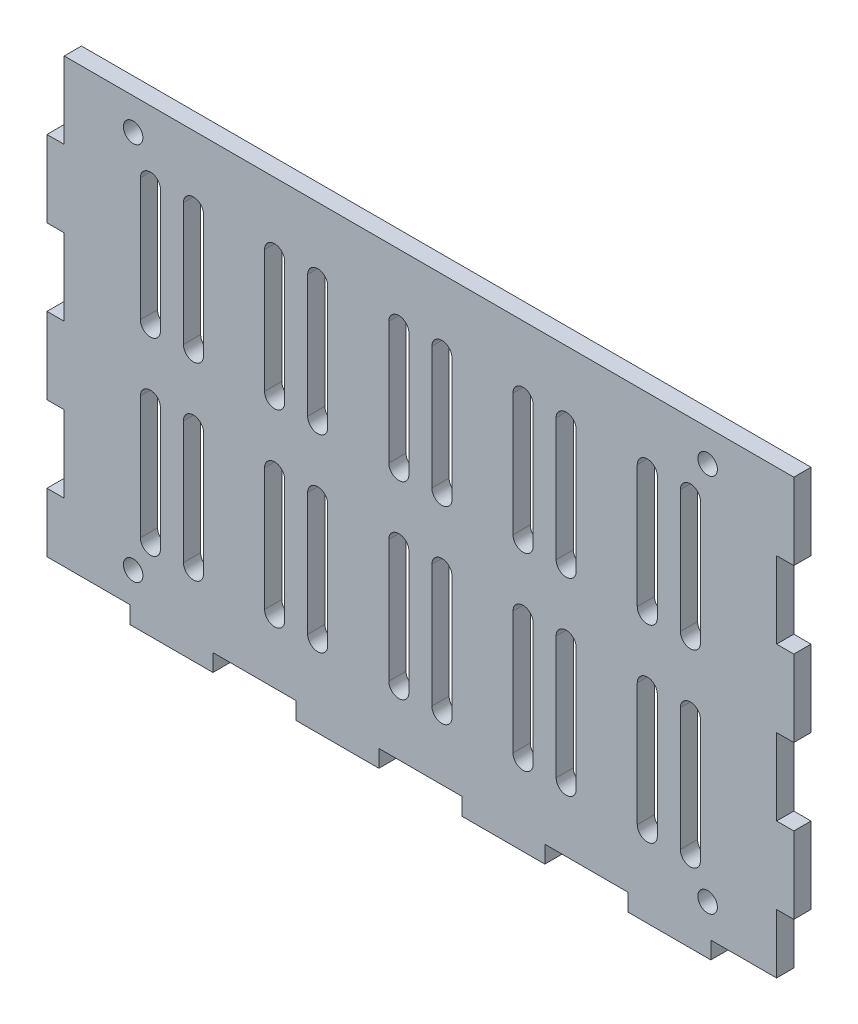
SolidWorks part; units mm, degrees
material "Acrylic (Medium-high impact)"
ref_plane "Front Plane" through (0, 0, 0) normal (0, 0, 1) x (1, 0, 0)
ref_plane "Top Plane" through (0, 0, 0) normal (0, 1, 0) x (1, 0, 0)
ref_plane "Right Plane" through (0, 0, 0) normal (1, 0, 0) x (0, 0, -1)
sketch "Sketch1" plane through (0, 0, 0) normal (0, 0, 1) x (1, 0, 0)
  line L1 (0, 0) -> (130, 0)
  line L2 (0, 0) -> (0, 80)
  line L3 (0, 80) -> (130, 80)
  line L4 (130, 0) -> (130, 80)
  dimension "D1" = 130
  dimension "D2" = 80
extrude "Boss-Extrude1" add sketch "Sketch1" along normal blind 3
sketch "Sketch2" plane through (0, 0, 3) normal (0, 0, 1) x (1, 0, 0)
  line L61 (14.4444, 3) -> (28.8889, 3) construction
  line L62 (0, 0) -> (14.4444, 0)
  line L67 (0, 0) -> (0, 3)
  line L72 (0, 3) -> (14.4444, 3)
  line L77 (14.4444, 0) -> (14.4444, 3)
  line L97 (28.8889, 0) -> (28.8889, 3)
  line L98 (28.8889, 0) -> (43.3333, 0)
  line L107 (43.3333, 0) -> (43.3333, 3)
  line L115 (28.8889, 3) -> (43.3333, 3)
  line L117 (43.3333, 3) -> (57.7778, 3) construction
  line L123 (57.7778, 0) -> (57.7778, 3)
  line L128 (57.7778, 0) -> (72.2222, 0)
  line L129 (72.2222, 0) -> (72.2222, 3)
  line L131 (57.7778, 3) -> (72.2222, 3)
  line L132 (72.2222, 3) -> (86.6667, 3) construction
  line L133 (86.6667, 0) -> (86.6667, 3)
  line L134 (86.6667, 0) -> (101.1111, 0)
  line L135 (101.1111, 0) -> (101.1111, 3)
  line L136 (86.6667, 3) -> (101.1111, 3)
  line L137 (101.1111, 3) -> (115.5556, 3) construction
  line L138 (115.5556, 0) -> (115.5556, 3)
  line L139 (115.5556, 0) -> (130, 0)
  line L142 (130, 0) -> (130, 80) construction
  line L143 (0, 80) -> (0, 0) construction
  line L144 (0, 13.3333) -> (3, 13.3333)
  line L145 (0, 13.3333) -> (0, 26.6667)
  line L146 (130, 3) -> (144.4444, 3) construction
  line L147 (0, 26.6667) -> (3, 26.6667)
  line L148 (3, 13.3333) -> (3, 26.6667)
  line L149 (3, 13.3333) -> (3, 0) construction
  line L150 (0, 40) -> (0, 53.3333)
  line L151 (0, 40) -> (3, 40)
  line L152 (3, 40) -> (3, 53.3333)
  line L153 (0, 53.3333) -> (3, 53.3333)
  line L154 (3, 40) -> (3, 26.6667) construction
  line L155 (0, 66.6667) -> (0, 80)
  line L156 (0, 66.6667) -> (3, 66.6667)
  line L157 (3, 66.6667) -> (3, 80)
  line L158 (0, 80) -> (3, 80)
  line L159 (3, 66.6667) -> (3, 53.3333) construction
  line L160 (130, 80) -> (0, 80) construction
  line L161 (127, 80) -> (127, 66.6667) construction
  line L162 (127, 40) -> (127, 26.6667)
  line L163 (127, 66.6667) -> (130, 66.6667)
  line L164 (127, 66.6667) -> (127, 53.3333)
  line L165 (127, 53.3333) -> (130, 53.3333)
  line L166 (130, 66.6667) -> (130, 53.3333)
  line L167 (127, 40) -> (130, 40)
  line L168 (130, 40) -> (130, 26.6667)
  line L169 (127, 26.6667) -> (130, 26.6667)
  line L170 (127, 53.3333) -> (127, 40) construction
  line L172 (127, 13.3333) -> (130, 13.3333)
  line L173 (130, 13.3333) -> (130, 0)
  line L175 (127, 26.6667) -> (127, 13.3333) construction
  line L183 (115.5556, 3) -> (130, 3) [skipped]
  line L184 (130, 0) -> (130, 3) [skipped]
  line L185 (127, 13.3333) -> (127, 3)
  line L186 (127, 3) -> (115.5556, 3)
  line L187 (127, 0) -> (130, 0) [skipped]
  line L188 (127, 13.3333) -> (127, 0) [skipped]
  dimension "D2" = 3
  dimension "D4" = 3
  dimension "D6" = 3
  dimension "D1" = 5
  dimension "D3" = 3
  dimension "D5" = 3
extrude "Cut tabs" cut sketch "Sketch2" against normal through all
sketch "Sketch3" plane through (0, 0, 3) normal (0, 0, 1) x (1, 0, 0)
  line L0 (0, 66.6667) -> (0, 53.3333) construction
  line L1 (130, 80) -> (3, 80) construction
  line L2 (0, 66.6667) -> (130, 66.6667) construction
  line L3 (65, 66.6667) -> (65, 50066.6667) construction
  line L4 (14.4444, 3) -> (0, 3) construction
  line L5 (15, 74.5) -> (115, 74.5) construction
  line L6 (15, 74.5) -> (15, 8.5) construction
  line L7 (15, 8.5) -> (115, 8.5) construction
  line L8 (115, 74.5) -> (115, 8.5) construction
  circle A0 centre (15, 74.5) radius 1.7
  circle A1 centre (115, 74.5) radius 1.7
  circle A2 centre (15, 8.5) radius 1.7
  circle A3 centre (115, 8.5) radius 1.7
  point P10 (65, 66.6667)
  dimension "D1" = 3.4
  dimension "D2" = 15
  dimension "D3" = 5.5
  dimension "D4" = 5.5
extrude "Cornerpiece holes" cut sketch "Sketch3" against normal up to next
sketch "Sketch4" plane through (0, 0, 3) normal (0, 0, 1) x (1, 0, 0)
  line L0 (18, 14) -> (18, 35.375) construction
  line L1 (16.25, 14) -> (16.25, 35.375)
  line L2 (19.75, 14) -> (19.75, 35.375)
  line L3 (18, 46.875) -> (18, 68.25) construction
  line L4 (16.25, 46.875) -> (16.25, 68.25)
  line L5 (19.75, 46.875) -> (19.75, 68.25)
  line L6 (25.5, 14) -> (25.5, 35.375) construction
  line L7 (23.75, 14) -> (23.75, 35.375)
  line L8 (27.25, 14) -> (27.25, 35.375)
  line L9 (25.5, 46.875) -> (25.5, 68.25) construction
  line L10 (23.75, 46.875) -> (23.75, 68.25)
  line L11 (27.25, 46.875) -> (27.25, 68.25)
  line L13 (130, 80) -> (3, 80) construction
  line L14 (14.4444, 3) -> (0, 3) construction
  line L15 (41.375, 14) -> (41.375, 35.375)
  line L17 (37.875, 14) -> (37.875, 35.375)
  line L18 (48.875, 14) -> (48.875, 35.375)
  line L19 (45.375, 14) -> (45.375, 35.375)
  line L20 (48.875, 46.875) -> (48.875, 68.25)
  line L21 (45.375, 46.875) -> (45.375, 68.25)
  line L22 (41.375, 46.875) -> (41.375, 68.25)
  line L23 (37.875, 46.875) -> (37.875, 68.25)
  line L24 (39.625, 14) -> (39.625, 35.375) construction
  line L25 (39.625, 46.875) -> (39.625, 68.25) construction
  line L26 (47.125, 14) -> (47.125, 35.375) construction
  line L27 (47.125, 46.875) -> (47.125, 68.25) construction
  line L28 (63, 14) -> (63, 35.375)
  line L29 (59.5, 14) -> (59.5, 35.375)
  line L30 (70.5, 14) -> (70.5, 35.375)
  line L31 (67, 14) -> (67, 35.375)
  line L32 (70.5, 46.875) -> (70.5, 68.25)
  line L33 (67, 46.875) -> (67, 68.25)
  line L34 (63, 46.875) -> (63, 68.25)
  line L35 (59.5, 46.875) -> (59.5, 68.25)
  line L36 (61.25, 14) -> (61.25, 35.375) construction
  line L37 (61.25, 46.875) -> (61.25, 68.25) construction
  line L38 (68.75, 14) -> (68.75, 35.375) construction
  line L39 (68.75, 46.875) -> (68.75, 68.25) construction
  line L40 (84.625, 14) -> (84.625, 35.375)
  line L41 (81.125, 14) -> (81.125, 35.375)
  line L42 (92.125, 14) -> (92.125, 35.375)
  line L43 (88.625, 14) -> (88.625, 35.375)
  line L44 (92.125, 46.875) -> (92.125, 68.25)
  line L45 (88.625, 46.875) -> (88.625, 68.25)
  line L46 (84.625, 46.875) -> (84.625, 68.25)
  line L47 (81.125, 46.875) -> (81.125, 68.25)
  line L48 (82.875, 14) -> (82.875, 35.375) construction
  line L49 (82.875, 46.875) -> (82.875, 68.25) construction
  line L50 (90.375, 14) -> (90.375, 35.375) construction
  line L51 (90.375, 46.875) -> (90.375, 68.25) construction
  line L52 (106.25, 14) -> (106.25, 35.375)
  line L53 (102.75, 14) -> (102.75, 35.375)
  line L54 (113.75, 14) -> (113.75, 35.375)
  line L55 (110.25, 14) -> (110.25, 35.375)
  line L56 (113.75, 46.875) -> (113.75, 68.25)
  line L57 (110.25, 46.875) -> (110.25, 68.25)
  line L58 (106.25, 46.875) -> (106.25, 68.25)
  line L59 (102.75, 46.875) -> (102.75, 68.25)
  line L60 (104.5, 14) -> (104.5, 35.375) construction
  line L61 (104.5, 46.875) -> (104.5, 68.25) construction
  line L62 (112, 14) -> (112, 35.375) construction
  line L63 (112, 46.875) -> (112, 68.25) construction
  line L64 (18, 24.6875) -> (3, 24.6875) construction
  line L65 (3, 13.3333) -> (3, 26.6667) construction
  line L66 (112, 24.6875) -> (127, 24.6875) construction
  line L67 (127, 26.6667) -> (127, 13.3333) construction
  line L68 (18, 35.375) -> (25.5, 35.375) construction
  arc A0 (16.25, 14) -> (19.75, 14) centre (18, 14) ccw
  arc A1 (19.75, 35.375) -> (16.25, 35.375) centre (18, 35.375) ccw
  arc A2 (16.25, 46.875) -> (19.75, 46.875) centre (18, 46.875) ccw
  arc A3 (19.75, 68.25) -> (16.25, 68.25) centre (18, 68.25) ccw
  arc A4 (23.75, 14) -> (27.25, 14) centre (25.5, 14) ccw
  arc A5 (27.25, 35.375) -> (23.75, 35.375) centre (25.5, 35.375) ccw
  arc A6 (23.75, 46.875) -> (27.25, 46.875) centre (25.5, 46.875) ccw
  arc A7 (27.25, 68.25) -> (23.75, 68.25) centre (25.5, 68.25) ccw
  arc A8 (37.875, 14) -> (41.375, 14) centre (39.625, 14) ccw
  arc A9 (41.375, 35.375) -> (37.875, 35.375) centre (39.625, 35.375) ccw
  arc A10 (45.375, 14) -> (48.875, 14) centre (47.125, 14) ccw
  arc A11 (48.875, 35.375) -> (45.375, 35.375) centre (47.125, 35.375) ccw
  arc A12 (45.375, 46.875) -> (48.875, 46.875) centre (47.125, 46.875) ccw
  arc A13 (48.875, 68.25) -> (45.375, 68.25) centre (47.125, 68.25) ccw
  arc A14 (37.875, 46.875) -> (41.375, 46.875) centre (39.625, 46.875) ccw
  arc A15 (41.375, 68.25) -> (37.875, 68.25) centre (39.625, 68.25) ccw
  arc A16 (59.5, 14) -> (63, 14) centre (61.25, 14) ccw
  arc A17 (63, 35.375) -> (59.5, 35.375) centre (61.25, 35.375) ccw
  arc A18 (67, 14) -> (70.5, 14) centre (68.75, 14) ccw
  arc A19 (70.5, 35.375) -> (67, 35.375) centre (68.75, 35.375) ccw
  arc A20 (67, 46.875) -> (70.5, 46.875) centre (68.75, 46.875) ccw
  arc A21 (70.5, 68.25) -> (67, 68.25) centre (68.75, 68.25) ccw
  arc A22 (59.5, 46.875) -> (63, 46.875) centre (61.25, 46.875) ccw
  arc A23 (63, 68.25) -> (59.5, 68.25) centre (61.25, 68.25) ccw
  arc A24 (81.125, 14) -> (84.625, 14) centre (82.875, 14) ccw
  arc A25 (84.625, 35.375) -> (81.125, 35.375) centre (82.875, 35.375) ccw
  arc A26 (88.625, 14) -> (92.125, 14) centre (90.375, 14) ccw
  arc A27 (92.125, 35.375) -> (88.625, 35.375) centre (90.375, 35.375) ccw
  arc A28 (88.625, 46.875) -> (92.125, 46.875) centre (90.375, 46.875) ccw
  arc A29 (92.125, 68.25) -> (88.625, 68.25) centre (90.375, 68.25) ccw
  arc A30 (81.125, 46.875) -> (84.625, 46.875) centre (82.875, 46.875) ccw
  arc A31 (84.625, 68.25) -> (81.125, 68.25) centre (82.875, 68.25) ccw
  arc A32 (102.75, 14) -> (106.25, 14) centre (104.5, 14) ccw
  arc A33 (106.25, 35.375) -> (102.75, 35.375) centre (104.5, 35.375) ccw
  arc A34 (110.25, 14) -> (113.75, 14) centre (112, 14) ccw
  arc A35 (113.75, 35.375) -> (110.25, 35.375) centre (112, 35.375) ccw
  arc A36 (110.25, 46.875) -> (113.75, 46.875) centre (112, 46.875) ccw
  arc A37 (113.75, 68.25) -> (110.25, 68.25) centre (112, 68.25) ccw
  arc A38 (102.75, 46.875) -> (106.25, 46.875) centre (104.5, 46.875) ccw
  arc A39 (106.25, 68.25) -> (102.75, 68.25) centre (104.5, 68.25) ccw
  point P2 (18, 24.6875)
  point P7 (18, 57.5625)
  point P14 (25.5, 24.6875)
  point P21 (25.5, 57.5625)
  point P36 (39.625, 24.6875)
  point P41 (39.625, 57.5625)
  point P48 (47.125, 24.6875)
  point P55 (47.125, 57.5625)
  point P64 (61.25, 24.6875)
  point P69 (61.25, 57.5625)
  point P76 (68.75, 24.6875)
  point P83 (68.75, 57.5625)
  point P92 (82.875, 24.6875)
  point P97 (82.875, 57.5625)
  point P104 (90.375, 24.6875)
  point P111 (90.375, 57.5625)
  point P120 (104.5, 24.6875)
  point P125 (104.5, 57.5625)
  point P132 (112, 24.6875)
  point P139 (112, 57.5625)
  dimension "D3" = 10
  dimension "D5" = 8
  dimension "D1" = 3.5
  dimension "D2" = 4
  dimension "D4" = 11
  dimension "D7" = 15
  dimension "D6" = 5
extrude "Cooling slots" cut sketch "Sketch4" against normal up to next
other "Width tolerance" face at (128.5, 53.3333, 1.5) face at (128.5, 26.6667, 1.5) face at (128.5, 13.3333, 1.5) face at (128.5, 40, 1.5) face at (128.5, 66.6667, 1.5) face at (115.5556, 1.5, 1.5) face at (86.6667, 1.5, 1.5) face at (57.7778, 1.5, 1.5) face at (28.8889, 1.5, 1.5) face at (14.4444, 1.5, 1.5) face at (43.3333, 1.5, 1.5) face at (72.2222, 1.5, 1.5) face at (101.1111, 1.5, 1.5) face at (1.5, 26.6667, 1.5) face at (1.5, 13.3333, 1.5) face at (1.5, 40, 1.5) face at (1.5, 53.3333, 1.5) face at (1.5, 66.6667, 1.5) parameters "D1"=0
equation "\"wall_thickness\"= 3mm"
equation "\"D1@Boss-Extrude1\"=\"wall_thickness\""
equation "\"slot_width_tolerance\"= 0.0mm"
equation "\"slot_depth\"= 3mm"
equation "\"D2@Sketch2\"=\"slot_depth\""
equation "\"D4@Sketch2\"=\"slot_depth\""
equation "\"D6@Sketch2\"=\"slot_depth\""
equation "\"D2@Sketch3\"=12.00mm+\"slot_depth\""
equation "\"D1@Width tolerance\" = \"slot_width_tolerance\""
